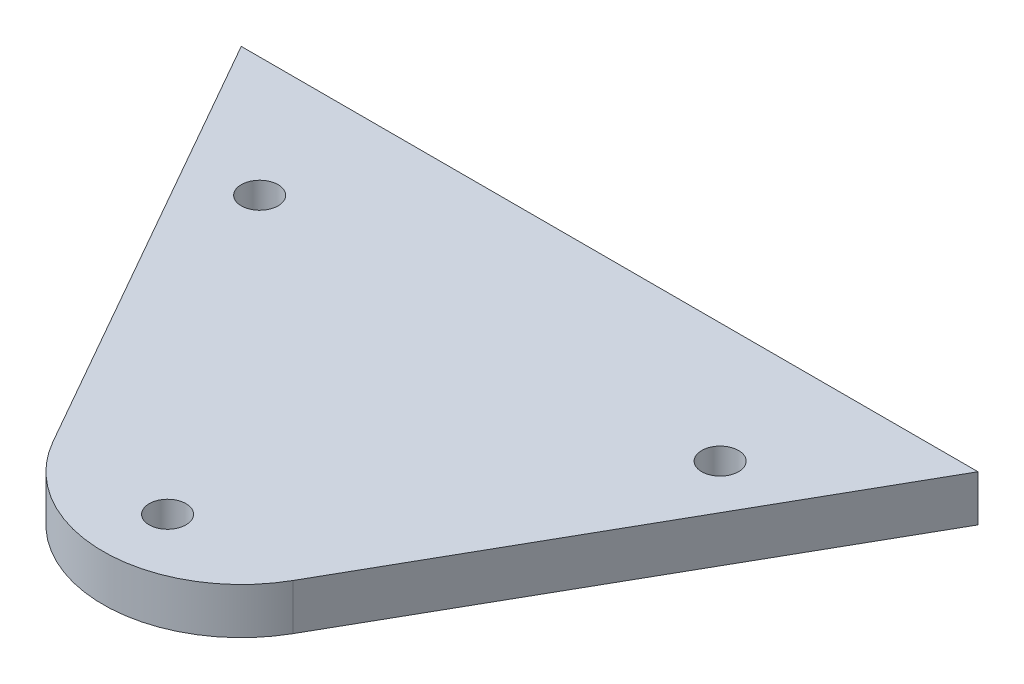
SolidWorks part; units mm, degrees
ref_plane "Front Plane" through (0, 0, 0) normal (0, 0, 1) x (1, 0, 0)
ref_plane "Top Plane" through (0, 0, 0) normal (0, 1, 0) x (1, 0, 0)
ref_plane "Right Plane" through (0, 0, 0) normal (1, 0, 0) x (0, 0, -1)
sketch "Sketch1" plane through (0, 0, 0) normal (0, 1, 0) x (1, 0, 0)
  line L3 (40, 48) -> (-40, 48)
  line L6 (-40, 48) -> (-13.0394, 0.5856)
  line L7 (13.0394, 0.5856) -> (40, 48)
  arc A0 (-13.0394, 0.5856) -> (13.0394, 0.5856) centre (0, 8) ccw
  point P0 (0, 48)
  point P6 (0, 0)
  point P7 (0, -7)
  point P8 (0, 0)
  dimension "D4" = 15
  dimension "D1" = 80
  dimension "D2" = 55
  dimension "D3" = 7
extrude "Boss-Extrude1" add sketch "Sketch1" along normal blind 5
sketch "Sketch2" plane through (0, 5, 0) normal (0, 1, 0) x (1, 0, 0)
  circle A0 centre (-25, 35) radius 2
  point P2 (-25, 37.5708)
  point P11 (0, 0)
  dimension "D3" = 4
  dimension "D1" = 25
  dimension "D2" = 35
extrude "Cut-Extrude1" cut sketch "Sketch2" against normal up to next
mirror "Mirror1" about plane through (0, 0, 0) normal (1, 0, 0) of "Cut-Extrude1"
sketch "Sketch3" plane through (0, 5, 0) normal (0, 1, 0) x (1, 0, 0)
  circle A0 centre (0, 0) radius 2
  point P2 (0, 0)
  point P4 (0, 0)
  dimension "D1" = 4
extrude "Cut-Extrude2" cut sketch "Sketch3" against normal up to next
